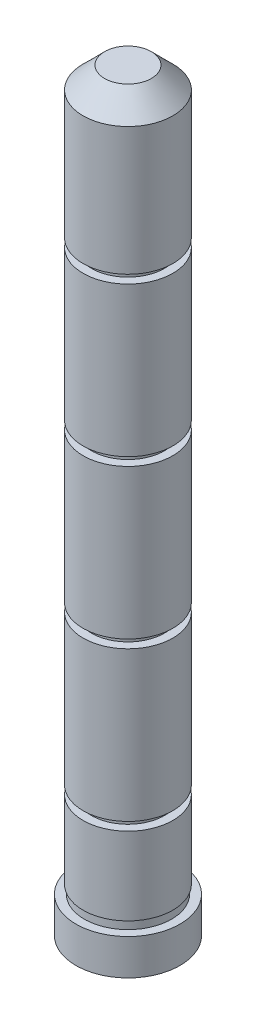
SolidWorks part; units mm, degrees
ref_plane "FP" through (0, 0, 0) normal (0, 0, 1) x (1, 0, 0)
ref_plane "TP" through (0, 0, 0) normal (0, 1, 0) x (1, 0, 0)
ref_plane "RP" through (0, 0, 0) normal (1, 0, 0) x (0, 0, -1)
sketch "Sketch1" plane through (0, 0, 0) normal (0, 0, 1) x (1, 0, 0)
  line L0 (0, 0) -> (14.5, 0)
  line L2 (12.5, 34) -> (10.15, 34)
  line L3 (10.15, 34) -> (10.15, 36.35)
  line L4 (10.15, 36.35) -> (12.5, 36.35)
  line L5 (12.5, 36.35) -> (12.5, 78)
  line L6 (12.5, 78) -> (10.15, 78)
  line L7 (10.15, 78) -> (10.15, 80.35)
  line L8 (10.15, 80.35) -> (12.5, 80.35)
  line L9 (12.5, 80.35) -> (12.5, 122)
  line L10 (12.5, 122) -> (10.15, 122)
  line L11 (10.15, 122) -> (10.15, 124.35)
  line L12 (10.15, 124.35) -> (12.5, 124.35)
  line L13 (12.5, 124.35) -> (12.5, 166)
  line L14 (12.5, 166) -> (10.15, 166)
  line L15 (10.15, 166) -> (10.15, 168.35)
  line L16 (10.15, 168.35) -> (12.5, 168.35)
  line L17 (12.5, 168.35) -> (12.5, 210)
  line L18 (12.5, 210) -> (0, 210)
  line L20 (14.5, 0) -> (14.5, 10)
  line L21 (14.5, 10) -> (12.15, 10)
  line L22 (12.15, 10) -> (12.15, 12.35)
  line L23 (12.15, 12.35) -> (12.5, 12.35)
  line L24 (12.5, 12.35) -> (12.5, 34)
  line L25 (0, 210) -> (0, 0)
  dimension "D3" = 2.35
  dimension "D4" = 210
  dimension "D1" = 14.5
  dimension "D5" = 10
  dimension "D6" = 12.5
  dimension "D2" = 34
revolve "Revolve1" add sketch "Sketch1" angle 360 about L25
chamfer "Chamfer1" distance 6 angle 45 1 edges at (-12.5, 210, 0)
equation "\"D\" = 25"
equation "\"L\"= 210"
equation "\"L1\"= 44"
equation "\"L2\"= 6"
equation "\"D2\"= 29"
equation "\"K\"= 10"
equation "\"M\"= 8"
equation "\"D4@Sketch1\"=\"L\""
equation "\"D1@Sketch1\"=\"D2\"/2"
equation "\"D5@Sketch1\"=\"K\""
equation "\"D6@Sketch1\"=\"D\"/2"
equation "\"D2@Sketch1\"=\"L1\"-\"K\""
equation "\"D1@Chamfer1\"=\"L2\""
